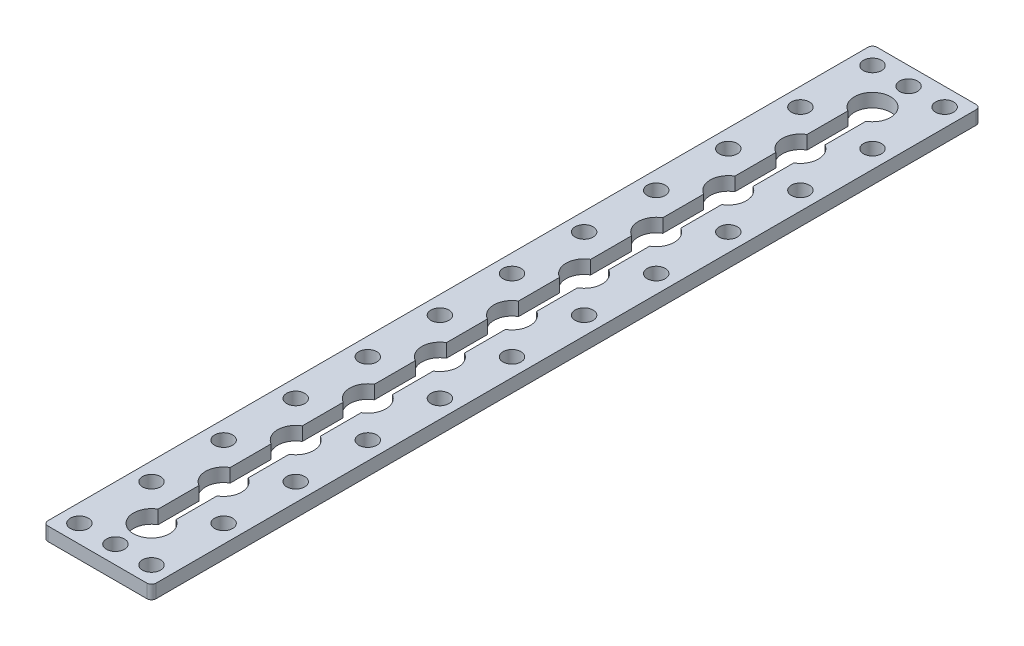
SolidWorks part; units mm, degrees
material "6061 Alloy"
ref_plane "Front Plane" through (0, 0, 0) normal (0, 0, 1) x (1, 0, 0)
ref_plane "Top Plane" through (0, 0, 0) normal (0, 1, 0) x (1, 0, 0)
ref_plane "Right Plane" through (0, 0, 0) normal (1, 0, 0) x (0, 0, -1)
sketch "Sketch1" plane through (0, 0, 0) normal (0, 1, 0) x (1, 0, 0)
  line L1 (12, -92) -> (-12, -92)
  line L2 (12, -92) -> (12, 92)
  line L3 (12, 92) -> (-12, 92)
  line L4 (-12, -92) -> (-12, 92)
  line L5 (12, -92) -> (-12, 92) construction
  line L6 (12, 92) -> (-12, -92) construction
  point P0 (0, 0)
  dimension "D1" = 184
  dimension "D2" = 24
extrude "Boss-Extrude1" add sketch "Sketch1" along normal blind 3
sketch "Sketch2" plane through (0, 3, 0) normal (0, 1, 0) x (1, 0, 0)
  line L0 (12, 92) -> (-12, 92) construction
  point P0 (-8, 88)
  point P1 (0, 88)
  point P2 (8, 88)
  point P3 (-8, 80)
  point P4 (8, 80)
  point P5 (-8, 72)
  point P6 (8, 72)
  point P7 (-8, 56)
  point P8 (8, 56)
  point P9 (8, 40)
  point P13 (8, 8)
  point P14 (-8, 8)
  point P15 (-8, 24)
  point P16 (8, 24)
  point P17 (0, 0)
  point P18 (0, 0)
  point P19 (-8, 40)
  point P20 (-16.7575, 15.7692)
  point P21 (0, 0)
  point P22 (0, 0)
  dimension "D1" = 4
  dimension "D2" = 16
  dimension "D3" = 8
  dimension "D4" = 8
  dimension "D5" = 8
  dimension "D6" = 16
  dimension "D7" = 16
  dimension "D8" = 16
  dimension "D9" = 16
hole_wizard "Ø4.0 (4) Diameter Hole1" positions "Sketch3" profile "Sketch4" hole size "Ø4.0" standard "GB" end condition through all
sketch "Sketch3" plane through (0, 3, 0) normal (0, 1, 0) x (1, 0, 0)
  point P0 (-8, 88)
  point P3 (0, 88)
  point P6 (8, 88)
  point P15 (-8, 72)
  point P18 (-8, 56)
  point P21 (8, 56)
  point P24 (8, 72)
  point P28 (-8, 40)
  point P31 (8, 40)
  point P35 (-8, 24)
  point P38 (-8, 8)
  point P41 (8, 8)
  point P44 (8, 24)
sketch "Sketch4" plane through (-8, 3, -88) normal (1, 0, 0) x (0, 0, 1)
  line L0 (0, 0) -> (0, 3)
  line L1 (0, 3) -> (2, 3)
  line L2 (2, 3) -> (2, 0)
  line L5 (2, 0) -> (0, 0)
  line L11 (0, -6.35) -> (0, 107.95) construction
  dimension "Thru Hole Dia." = 4
  dimension "Thru Hole Depth" = 3
mirror "Mirror1" about plane through (0, 0, 0) normal (0, 0, 1) of "Ø4.0 (4) Diameter Hole1"
sketch "Sketch6" plane through (0, 3, 0) normal (0, 1, 0) x (1, 0, 0)
  point P0 (0, 80)
  point P1 (0, 0)
hole_wizard "Ø8.0 (8) Diameter Hole1" positions "Sketch7" profile "Sketch8" hole size "Ø8.0" standard "GB" end condition through all
sketch "Sketch7" plane through (0, 3, 0) normal (0, 1, 0) x (1, 0, 0)
  point P0 (0, 80)
sketch "Sketch8" plane through (0, 3, -80) normal (1, 0, 0) x (0, 0, 1)
  line L0 (0, 0) -> (0, 3)
  line L1 (0, 3) -> (4, 3)
  line L2 (4, 3) -> (4, 0)
  line L5 (4, 0) -> (0, 0)
  line L11 (0, -6.35) -> (0, 107.95) construction
  dimension "Thru Hole Dia." = 8
  dimension "Thru Hole Depth" = 3
pattern_linear "LPattern1" count 11 spacing 16 along (0, 0, 1) of "Ø8.0 (8) Diameter Hole1"
sketch "Sketch9" plane through (0, 3, 0) normal (0, 1, 0) x (1, 0, 0)
  line L0 (-12, -92) -> (12, -92) construction
  line L1 (-2, 80) -> (2, 80)
  line L2 (-2, 80) -> (-2, -80)
  line L3 (-2, -80) -> (2, -80)
  line L4 (2, 80) -> (2, -80)
  line L5 (-2, 80) -> (2, -80) construction
  line L6 (-2, -80) -> (2, 80) construction
  point P4 (0, 0)
  point P8 (-2.8486, -16)
  point P9 (0, 0)
  point P11 (0, 0)
  dimension "D1" = 4
  dimension "D2" = 12
extrude "Cut-Extrude1" cut sketch "Sketch9" against normal blind 3
fillet "Fillet1" radius 1 4 edges at (12, 1.5, -92) (-12, 1.5, -92) (12, 1.5, 92) (-12, 1.5, 92)
equation "\"D8@Sketch2\"=\"D7@Sketch2\""
equation "\"D9@Sketch2\"=\"D8@Sketch2\""
